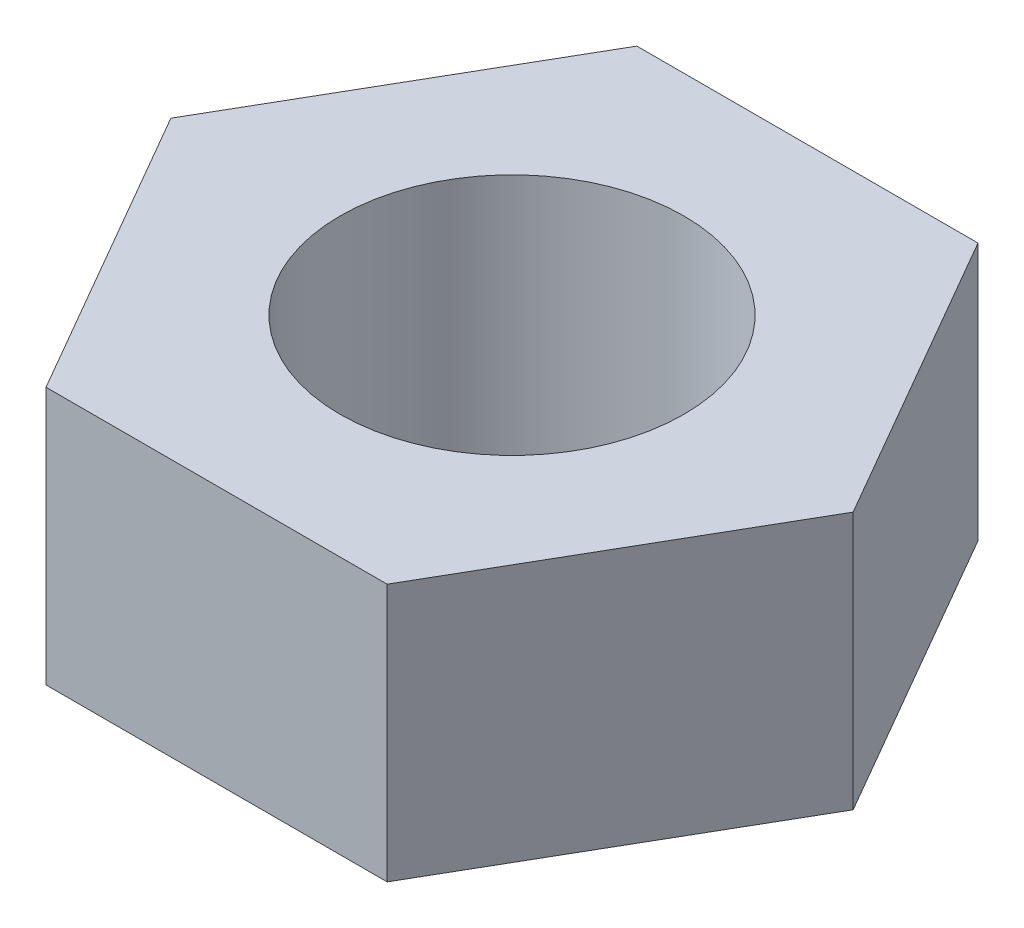
SolidWorks part; units mm, degrees
other "Frame Rear Nut"
ref_plane "Front Plane" through (0, 0, 0) normal (0, 0, 1) x (1, 0, 0)
ref_plane "Top Plane" through (0, 0, 0) normal (0, 1, 0) x (1, 0, 0)
ref_plane "Right Plane" through (0, 0, 0) normal (1, 0, 0) x (0, 0, -1)
sketch3d "Base Outline Sketch datum points"
  point P0 (0, -159.9, 0)
  point P1 (10, -159.9, 0)
  point P2 (0, -159.9, -10)
ref_plane "Base Outline Sketch plane" through (0, -159.9, 0) normal (0, 1, 0) x (1, 0, 0)
sketch "Base Outline Sketch" plane through (0, -159.9, 0) normal (0, 1, 0) x (1, 0, 0)
  line L0 (-53.1162, -50) -> (-54.7039, -52.75)
  line L1 (-54.7039, -47.25) -> (-53.1162, -50)
  line L2 (-54.7039, -52.75) -> (-57.8794, -52.75)
  line L3 (-57.8794, -47.25) -> (-54.7039, -47.25)
  line L4 (-57.8794, -52.75) -> (-59.4671, -50)
  line L5 (-59.4671, -50) -> (-57.8794, -47.25)
  circle A0 centre (-56.2917, -50) radius 1.6
extrude "Base Outline" add sketch "Base Outline Sketch" along normal blind 2.4 separate body
